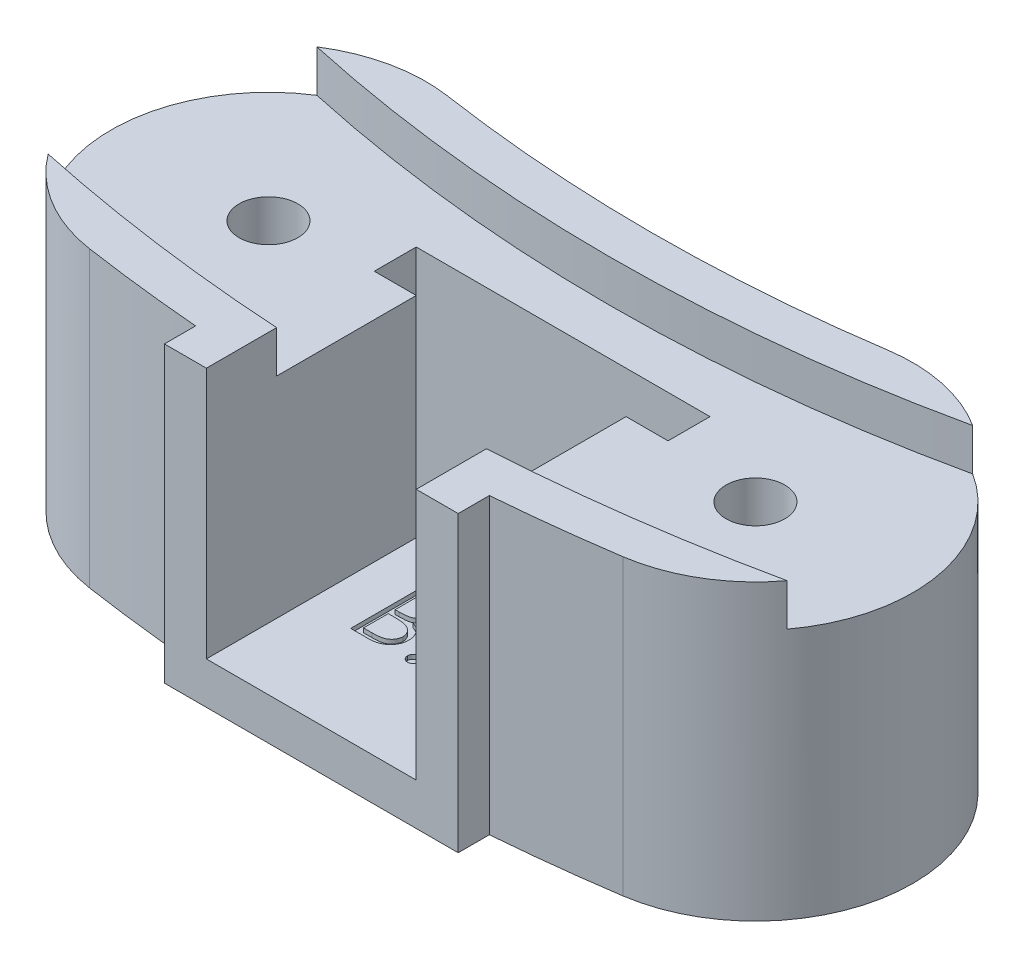
SolidWorks part; units mm, degrees
material "ABS"
ref_plane "Front Plane" through (0, 0, 0) normal (0, 0, 1) x (1, 0, 0)
ref_plane "Top Plane" through (0, 0, 0) normal (0, 1, 0) x (1, 0, 0)
ref_plane "Right Plane" through (0, 0, 0) normal (1, 0, 0) x (0, 0, -1)
sketch "Sketch2" plane through (0, 0, 0) normal (0, 1, 0) x (1, 0, 0)
  line L1 (0, 0) -> (0, 91.8096) construction
  line L3 (0, 78.5) -> (-14.8004, -20.5315) construction
  line L4 (0, 78.5) -> (14.5313, -18.7312) construction
  arc A0 (-18.3762, 9.9193) -> (18.3762, 9.9193) centre (0, 78.5) ccw
  arc A1 (-22.2584, -4.5696) -> (22.2584, -4.5696) centre (0, 78.5) ccw
  circle A4 centre (0, 78.5) radius 78.5 construction
  circle A6 centre (0, 78.5) radius 73 construction
  circle A7 centre (0, 78.5) radius 84 construction
  circle A8 centre (0, 78.5) radius 86 construction
  circle A9 centre (0, 78.5) radius 71 construction
  circle A11 centre (11.603, 0.8623) radius 1.4
  circle A12 centre (-11.603, 0.8623) radius 1.4
  arc A13 (-10.4945, 8.2799) -> (-12.7116, -6.5554) centre (-11.603, 0.8623) ccw
  arc A14 (12.7116, -6.5554) -> (10.4945, 8.2799) centre (11.603, 0.8623) ccw
  point P6 (71, 78.5)
  point P13 (86, 78.5)
  dimension "D1" = 146
  dimension "D2" = 168
  dimension "D3" = 5.5
  dimension "D8" = 142
  dimension "D9" = 86
  dimension "D6" = 2
  dimension "D12" = 2.8
  dimension "D13" = 2.8
  dimension "D4" = 8.5
  dimension "D5" = 8.5
  dimension "D7" = 2
extrude "Boss-Extrude1" add sketch "Sketch2" along normal blind 12 contours A1 A14 A0 A13 A11 A12
sketch "Sketch14" plane through (0, 12, 0) normal (0, 1, 0) x (1, 0, 0)
  arc A0 (-15.626, 7.192) -> (15.626, 7.192) centre (0, 78.5) ccw
  arc A1 (-17.6056, -3.6343) -> (17.6056, -3.6343) centre (0, 78.5) ccw
  arc A2 (-12.7116, -6.5554) -> (12.7116, -6.5554) centre (0, 78.5) ccw construction
  arc A3 (-10.4945, 8.2799) -> (-12.7116, -6.5554) centre (-11.603, 0.8623) ccw construction
  arc A4 (-10.4945, 8.2799) -> (10.4945, 8.2799) centre (0, 78.5) ccw construction
  arc A9 (-10.4945, 8.2799) -> (10.4945, 8.2799) centre (0, 78.5) ccw
  arc A11 (-12.7116, -6.5554) -> (12.7116, -6.5554) centre (0, 78.5) ccw
  arc A12 (-10.4945, 8.2799) -> (-12.7116, -6.5554) centre (-11.603, 0.8623) ccw
  arc A13 (12.7116, -6.5554) -> (10.4945, 8.2799) centre (11.603, 0.8623) ccw construction
  arc A14 (12.7116, -6.5554) -> (10.4945, 8.2799) centre (11.603, 0.8623) ccw
  dimension "D2" = 84
  dimension "D3" = 73
extrude "Boss-Extrude5" add sketch "Sketch14" along normal blind 2 contours A11 A14 A1 A12 | A0 A14 A9 A12
ref_plane "Plane4" through (0, 6, 0) normal (0, 1, 0) x (1, 0, 0)
ref_plane "Plane1" through (0, 0, 7.7) normal (0, 0, 1) x (1, 0, 0)
sketch "Sketch3" plane through (0, 0, 7.7) normal (0, 0, 1) x (1, 0, 0)
  line L0 (0, 0) -> (0, 14)
  line L1 (12.7116, 14) -> (-12.7116, 14) construction
  line L2 (-7, 14) -> (7, 14)
  line L4 (7, 14) -> (7, 0)
  line L5 (7, 0) -> (-7, 0)
  line L6 (-7, 0) -> (-7, 14)
  line L9 (7, 14) -> (7, 11.338)
  circle A0 centre (0, 7) radius 7 construction
  dimension "D1" = 14
extrude "Boss-Extrude2" add sketch "Sketch3" against normal up to body and the other way blind 1 separate body contours L2 L4 L5 L6
sketch "Sketch15" plane through (0, 0, 8.7) normal (0, 0, 1) x (1, 0, 0)
  line L0 (-7, 12) -> (7, 12)
  line L1 (-7, 0) -> (-7, 14) construction
  line L2 (7, 14) -> (7, 0) construction
  line L3 (-7, 0) -> (-7, 14)
  line L4 (7, 14) -> (7, 0) construction
  line L5 (7, 14) -> (7, 0)
  line L6 (7, 0) -> (-7, 0) construction
  line L7 (7, 0) -> (-7, 0)
  line L8 (5, 14) -> (5, 2)
  line L9 (5, 2) -> (-5, 2)
  line L10 (-5, 2) -> (-5, 14)
  line M5 (7, 14) -> (-7, 14)
  dimension "D1" = 2
extrude "Cut-Extrude1" cut sketch "Sketch15" against normal blind 12 contours L10 L9 L8 L0 | L10 L0 L8 M5
sketch "Sketch16" plane through (0, 12, 0) normal (0, 1, 0) x (1, 0, 0)
  line L0 (-5, 3.3) -> (-7, 3.3)
  line L1 (-7, 3.3) -> (-7, 1.3)
  line L2 (-7, 1.3) -> (-5, 1.3)
  line L3 (-5, -5.3511) -> (-5, 3.3) construction
  line L4 (5, 3.3) -> (7, 3.3)
  line L5 (7, 3.3) -> (7, 1.3)
  line L6 (7, 1.3) -> (5, 1.3)
  line L7 (5, 3.3) -> (5, -8.7) construction
  line L8 (-5, 1.3) -> (-5, 3.3)
  line L9 (5, 1.3) -> (5, 3.3)
  dimension "D1" = 2
  dimension "D2" = 2
  dimension "D3" = 2
  dimension "D4" = 2
extrude "Cut-Extrude2" cut sketch "Sketch16" against normal up to surface (10 mm away) up to face at (0, 2, 2.7)
sketch "Sketch17" plane through (0, 2, 0) normal (0, 1, 0) x (1, 0, 0)
  text T0 "B.2\r\n"
extrude "Cut-Extrude3" cut sketch "Sketch17" against normal blind 0.2
